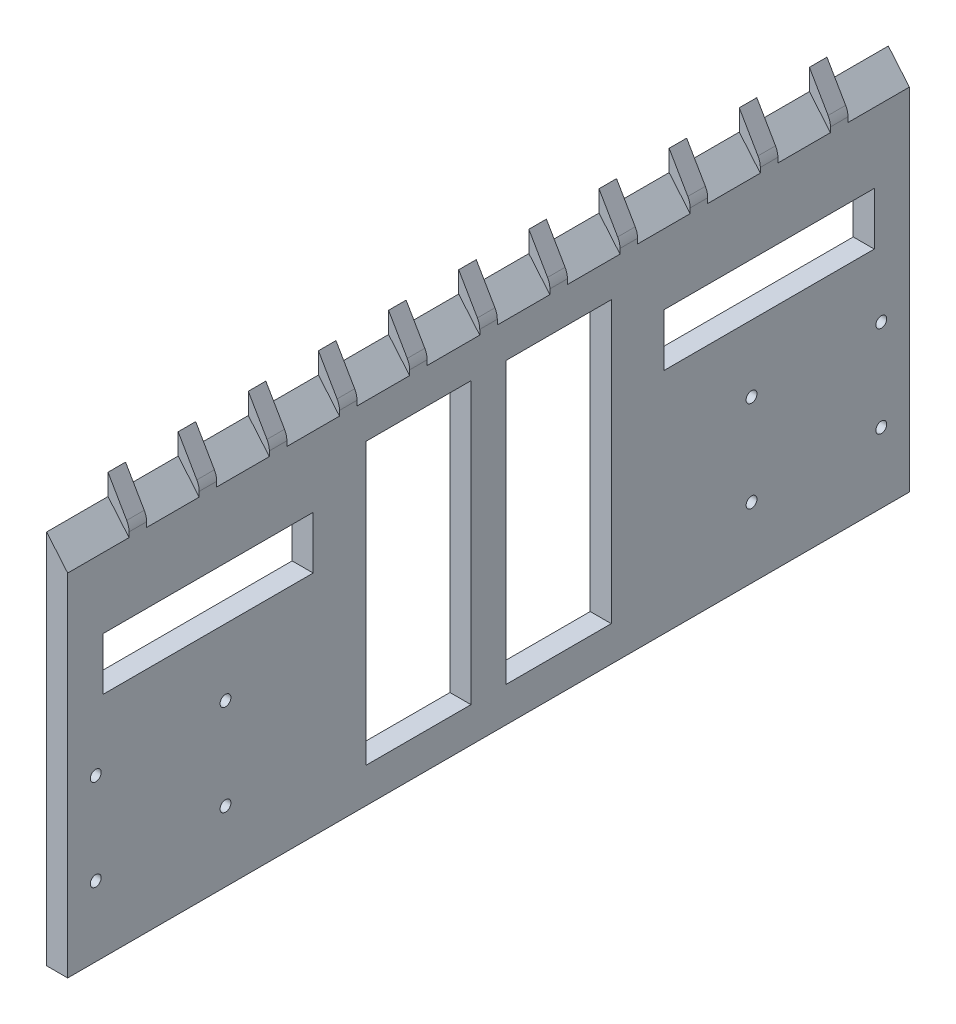
SolidWorks part; units mm, degrees
ref_plane "前视基准面" through (0, 0, 0) normal (0, 0, 1) x (1, 0, 0)
ref_plane "上视基准面" through (0, 0, 0) normal (0, 1, 0) x (1, 0, 0)
ref_plane "右视基准面" through (0, 0, 0) normal (1, 0, 0) x (0, 0, -1)
sketch "草图1" plane through (0, 0, 0) normal (1, 0, 0) x (0, 0, -1)
  line L1 (0, 0) -> (240, 0)
  line L2 (0, 0) -> (0, -100)
  line L3 (0, -100) -> (240, -100)
  line L4 (240, 0) -> (240, -100)
  dimension "D1" = 240
  dimension "D2" = 100
extrude "凸台-拉伸1" add sketch "草图1" along normal blind 6
sketch "草图2" plane through (6, 0, 0) normal (1, 0, 0) x (0, 0, -1)
  line L0 (0, 0) -> (0, -100) construction
  line L1 (8, -54) -> (45, -54) construction
  line L2 (8, -54) -> (8, -80) construction
  line L3 (8, -80) -> (45, -80) construction
  line L4 (45, -54) -> (45, -80) construction
  line L5 (240, 0) -> (0, 0) construction
  line L6 (120, 0) -> (120, -100) construction
  line L7 (0, -100) -> (240, -100) construction
  line L8 (195, -54) -> (195, -80) construction
  line L9 (232, -80) -> (195, -80) construction
  line L10 (232, -54) -> (232, -80) construction
  line L11 (232, -54) -> (195, -54) construction
  circle A0 centre (8, -54) radius 1.55
  circle A1 centre (45, -80) radius 1.55
  circle A2 centre (45, -54) radius 1.55
  circle A3 centre (8, -80) radius 1.55
  circle A4 centre (232, -80) radius 1.55
  circle A5 centre (195, -54) radius 1.55
  circle A6 centre (195, -80) radius 1.55
  circle A7 centre (232, -54) radius 1.55
  dimension "D5" = 3.1
  dimension "D1" = 8
  dimension "D2" = 54
  dimension "D3" = 37
  dimension "D4" = 26
extrude "切除-拉伸1" cut sketch "草图2" against normal through all
sketch "草图3" plane through (6, 0, 0) normal (1, 0, 0) x (0, 0, -1)
  line L0 (120, 0) -> (120, -100) construction
  line L1 (10, -20) -> (70, -20)
  line L2 (10, -20) -> (10, -35)
  line L3 (10, -35) -> (70, -35)
  line L4 (70, -20) -> (70, -35)
  line L5 (240, 0) -> (0, 0) construction
  line L6 (0, -100) -> (240, -100) construction
  line L7 (0, 0) -> (0, -100) construction
  line L8 (170, -20) -> (170, -35)
  line L9 (230, -35) -> (170, -35)
  line L10 (230, -20) -> (230, -35)
  line L11 (230, -20) -> (170, -20)
  dimension "D1" = 10
  dimension "D2" = 20
  dimension "D3" = 15
  dimension "D4" = 60
extrude "切除-拉伸2" cut sketch "草图3" against normal through all
sketch "草图4" plane through (6, 0, 0) normal (1, 0, 0) x (0, 0, -1)
  line L0 (120, 0) -> (120, -100) construction
  line L1 (85, -10) -> (115, -10)
  line L2 (85, -10) -> (85, -90)
  line L3 (85, -90) -> (115, -90)
  line L4 (115, -10) -> (115, -90)
  line L5 (240, 0) -> (0, 0) construction
  line L6 (0, -100) -> (240, -100) construction
  line L7 (0, 0) -> (0, -100) construction
  line L8 (125, -10) -> (125, -90)
  line L9 (155, -90) -> (125, -90)
  line L10 (155, -10) -> (155, -90)
  line L11 (155, -10) -> (125, -10)
  dimension "D1" = 10
  dimension "D2" = 10
  dimension "D3" = 85
  dimension "D4" = 30
extrude "切除-拉伸3" cut sketch "草图4" against normal through all contours L4 L1 L2 L3 | L8 L9 L10 L11
sketch "草图5" plane through (0, 0, 0) normal (-1, 0, 0) x (0, 0, 1)
  circle A0 centre (-195, -80) radius 3
  circle A1 centre (-232, -80) radius 3
  circle A2 centre (-195, -54) radius 3
  circle A3 centre (-232, -54) radius 3
  circle A4 centre (-45, -80) radius 3
  circle A5 centre (-8, -80) radius 3
  circle A6 centre (-8, -54) radius 3
  circle A7 centre (-45, -54) radius 3
  dimension "D1" = 6
extrude "切除-拉伸4" cut sketch "草图5" against normal blind 3
sketch "草图6" plane through (0, 0, 0) normal (0, 0, 1) x (1, 0, 0)
  line L0 (6, 0) -> (0, 0)
  line L1 (0, 0) -> (0, 7.1505)
  line L2 (0, 7.1505) -> (6, 0)
  dimension "D1" = 40
extrude "凸台-拉伸2" add sketch "草图6" against normal blind 240
ref_plane "基准面1" through (0, 0, -117.5) normal (0, 0, 1) x (1, 0, 0)
sketch "草图7" plane through (0, 0, -117.5) normal (0, 0, 1) x (1, 0, 0)
  line L0 (0, 7.1505) -> (0, 13.1505)
  line L7 (0, 13.1505) -> (6, 2.7582)
  line L9 (6, 2.7582) -> (6, 0)
  line L10 (6, 0) -> (0, 7.1505)
  dimension "D1" = 6
  dimension "D2" = 30
extrude "凸台-拉伸3" add sketch "草图7" against normal blind 5
pattern_linear "阵列(线性)1" count 6 spacing 20 along (0, 0, -1) count 6 spacing 20 along (0, 0, 1) of "凸台-拉伸3"
fillet "圆角1" radius 5 11 edges at (6, 2.7582, -40) (6, 2.7582, -20) (6, 2.7582, -60) (6, 2.7582, -100) (6, 2.7582, -80) (6, 2.7582, -120) (6, 2.7582, -140) (6, 2.7582, -160) (6, 2.7582, -180) (6, 2.7582, -200) (6, 2.7582, -220)
